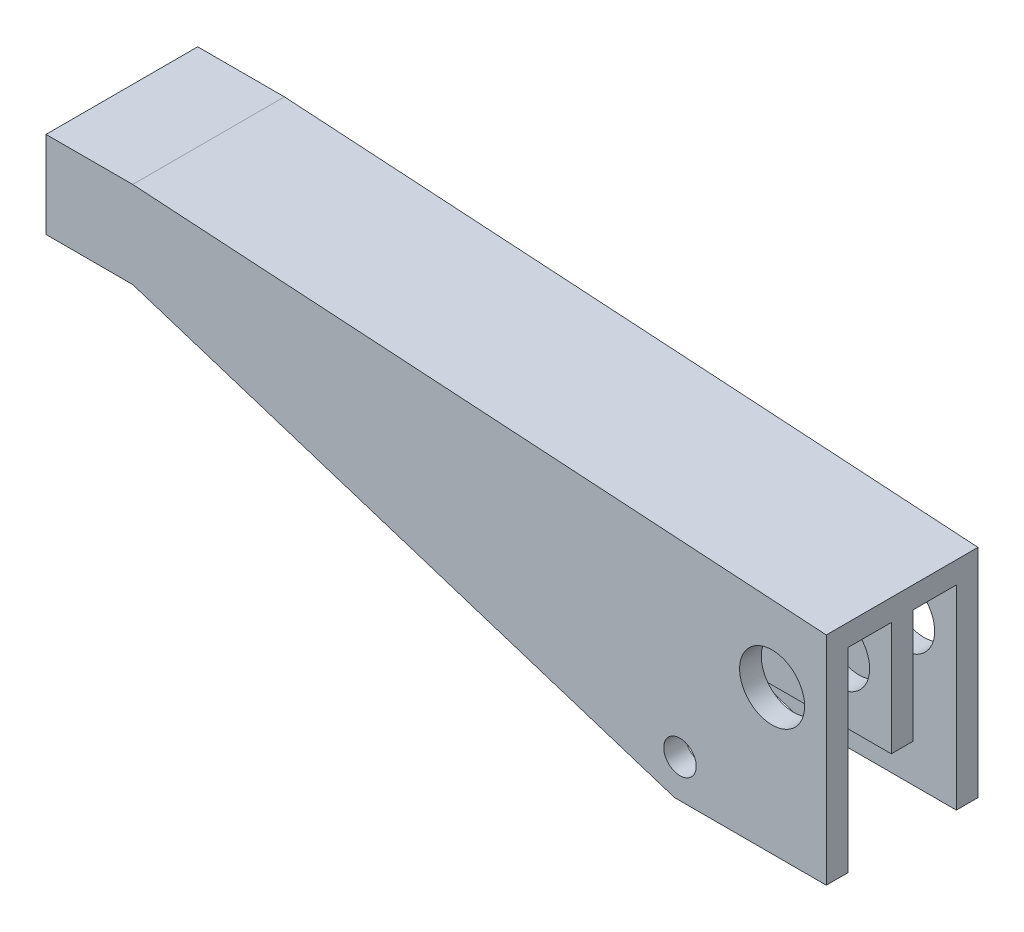
SolidWorks part; units mm, degrees
material "AISI 1045 Steel, cold drawn"
ref_plane "Front Plane" through (0, 0, 0) normal (0, 0, 1) x (1, 0, 0)
ref_plane "Top Plane" through (0, 0, 0) normal (0, 1, 0) x (1, 0, 0)
ref_plane "Right Plane" through (0, 0, 0) normal (1, 0, 0) x (0, 0, -1)
sketch "Sketch1" plane through (0, 0, 0) normal (0, 0, 1) x (1, 0, 0)
  line L0 (-914.4, 304.8) -> (-812.8, 304.8)
  line L1 (-914.4, 304.8) -> (-914.4, 203.2)
  line L2 (-914.4, 203.2) -> (-812.8, 203.2)
  line L4 (-177.8, 0) -> (0, 0)
  line L5 (0, 0) -> (0, 254)
  line L6 (0, 254) -> (-812.8, 304.8)
  line L7 (-812.8, 203.2) -> (-177.8, 0)
  dimension "D1" = 101.6
  dimension "D2" = 101.6
  dimension "D3" = 914.4
  dimension "D4" = 177.8
  dimension "D6" = 203.2
  dimension "D7" = 254
extrude "Boss-Extrude1" add sketch "Sketch1" against normal blind 25.4
ref_plane "Plane1" through (0, 0, 127) normal (0, 0, 1) x (1, 0, 0)
sketch "Sketch2" plane through (0, 0, 127) normal (0, 0, 1) x (1, 0, 0)
  line L8 (-812.8, 203.2) -> (-177.8, 0)
  line L10 (-177.8, 0) -> (0, 0)
  line L11 (0, 0) -> (0, 254)
  line L12 (0, 254) -> (-812.8, 304.8)
  line L13 (-812.8, 304.8) -> (-914.4, 304.8)
  line L14 (-914.4, 304.8) -> (-914.4, 203.2)
  line L15 (-914.4, 203.2) -> (-812.8, 203.2)
  line L16 (-812.8, 203.2) -> (-177.8, 0)
  line L18 (-177.8, 0) -> (0, 0)
  line L19 (0, 0) -> (0, 254)
  line L20 (0, 254) -> (-812.8, 304.8)
  line L21 (-812.8, 304.8) -> (-914.4, 304.8)
  line L22 (-914.4, 304.8) -> (-914.4, 203.2)
  line L23 (-914.4, 203.2) -> (-812.8, 203.2)
  dimension "D1" = 0
extrude "Boss-Extrude2" add sketch "Sketch2" along normal blind 25.4 separate body
sketch "Sketch3" plane through (0, 0, 152.4) normal (0, 0, 1) x (1, 0, 0)
  line L6 (-914.4, 279.4) -> (-914.4, 304.8)
  line L7 (-914.4, 304.8) -> (-812.8, 304.8)
  line L8 (-812.8, 304.8) -> (0, 254)
  line L9 (-25.4, 0) -> (-25.4, 230.1379)
  line L10 (-25.4, 230.1379) -> (-813.593, 279.4)
  line L11 (-813.593, 279.4) -> (-914.4, 279.4)
  line L12 (-25.4, 230.1379) -> (0, 228.5504)
  line L13 (-25.4, 230.1379) -> (-813.593, 279.4)
  line L14 (-813.593, 279.4) -> (-914.4, 279.4)
  line L15 (0, 0) -> (0, 254) construction
  line L16 (0, 228.5504) -> (0, 254)
  dimension "D1" = 25.4
extrude "Boss-Extrude3" add sketch "Sketch3" against normal up to surface (152.4 mm away) up to face at (-518.8857, 181.4286, 0)
ref_plane "Plane2" through (0, 0, 63.5) normal (0, 0, 1) x (1, 0, 0)
sketch "Sketch6" plane through (0, 0, 63.5) normal (0, 0, 1) x (1, 0, 0)
  line L8 (-812.8, 203.2) -> (-177.8, 0)
  line L10 (-177.8, 0) -> (0, 0)
  line L11 (0, 0) -> (0, 254)
  line L12 (0, 254) -> (-812.8, 304.8)
  line L13 (-812.8, 304.8) -> (-914.4, 304.8)
  line L14 (-914.4, 304.8) -> (-914.4, 203.2)
  line L15 (-914.4, 203.2) -> (-812.8, 203.2)
  line L16 (-812.8, 203.2) -> (-177.8, 0)
  line L18 (-177.8, 0) -> (0, 0)
  line L19 (0, 0) -> (0, 254)
  line L20 (0, 254) -> (-812.8, 304.8)
  line L21 (-812.8, 304.8) -> (-914.4, 304.8)
  line L22 (-914.4, 304.8) -> (-914.4, 203.2)
  line L23 (-914.4, 203.2) -> (-812.8, 203.2)
  dimension "D1" = 0
extrude "Boss-Extrude4" add sketch "Sketch6" along normal blind 12.7 and the other way blind 12.7
sketch "Sketch5" plane through (0, 0, 152.4) normal (0, 0, 1) x (1, 0, 0)
  line L1 (0, 228.5504) -> (-813.593, 279.4) construction
  line L2 (-177.8, 0) -> (0, 0) construction
  line L3 (0, 0) -> (0, 254) construction
  circle A0 centre (-63.5, 168.9696) radius 38.1
  circle A1 centre (-171.45, 44.45) radius 19.05
  point P2 (-25.4, 168.9696)
  point P5 (-63.5, 207.0696)
  point P9 (-171.45, 25.4)
  point P10 (-190.5, 44.45)
  point P13 (-101.6, 168.9696)
  point P21 (-152.4, 44.45)
  dimension "D1" = 25.4
  dimension "D3" = 76.2
  dimension "D6" = 38.1
  dimension "D2" = 25.4
  dimension "D4" = 25.4
  dimension "D5" = 50.8
extrude "Cut-Extrude1" cut sketch "Sketch5" against normal through all
sketch "Sketch7" plane through (0, 0, 76.2) normal (0, 0, 1) x (1, 0, 0)
  line L0 (-475.4562, 95.25) -> (0, 95.25)
  line L1 (0, 95.25) -> (0, 0)
  line L2 (0, 0) -> (-177.8, 0)
  line L3 (-177.8, 0) -> (0, 0) construction
  line L4 (0, 0) -> (0, 228.5504) construction
  line L5 (-812.8, 203.2) -> (-177.8, 0) construction
  line L6 (-475.4562, 95.25) -> (-177.8, 0)
  dimension "D1" = 95.25
extrude "Cut-Extrude2" cut sketch "Sketch7" against normal up to surface (25.4 mm away) up to face at (-152.4, 44.45, 50.8)
scale "Scale1" scale about centroid uniform scaling yes scale factor 2.84
